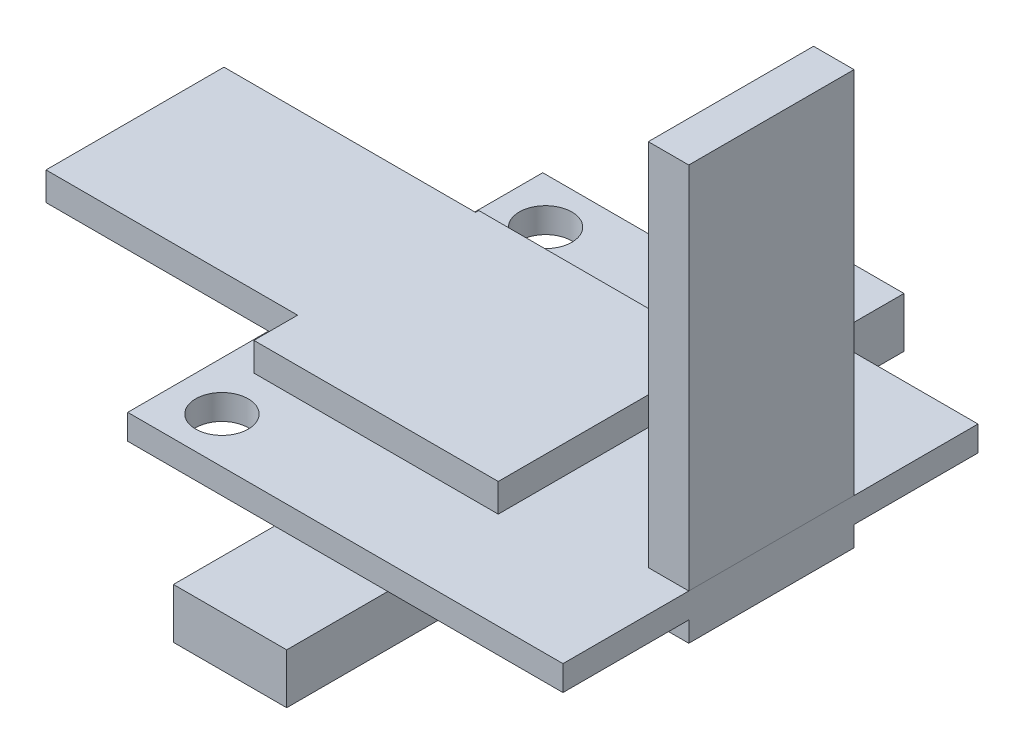
SolidWorks part; units mm, degrees
ref_plane "Front Plane" through (0, 0, 0) normal (0, 0, 1) x (1, 0, 0)
ref_plane "Top Plane" through (0, 0, 0) normal (0, 1, 0) x (1, 0, 0)
ref_plane "Right Plane" through (0, 0, 0) normal (1, 0, 0) x (0, 0, -1)
sketch "Sketch1" plane through (0, 0, 0) normal (0, 1, 0) x (1, 0, 0)
  line L0 (-13.6652, 0) -> (13.6652, 0) construction
  line L1 (-13.6652, 13.0302) -> (13.6652, 13.0302)
  line L2 (-13.6652, 13.0302) -> (-13.6652, -13.0302)
  line L3 (-13.6652, -13.0302) -> (13.6652, -13.0302)
  line L4 (13.6652, 13.0302) -> (13.6652, -13.0302)
  line L5 (-10.6172, 10.16) -> (-10.6172, 0) construction
  line L6 (-10.6172, 0) -> (-10.6172, -10.16) construction
  circle A0 centre (-10.6172, 10.16) radius 1.651
  circle A1 centre (-10.6172, -10.16) radius 1.651
  point P10 (-10.6172, 11.811)
  point P11 (-10.6172, -11.811)
  point P14 (-10.6172, 8.509)
  point P15 (-10.6172, -8.509)
  point P16 (-12.2682, 10.16)
  dimension "D3" = 3.302
  dimension "D1" = 27.3304
  dimension "D2" = 26.0604
  dimension "D4" = 23.622
  dimension "D5" = 17.018
  dimension "D6" = 1.397
extrude "Boss-Extrude1" add sketch "Sketch1" along normal blind 1.5748
sketch "Sketch2" plane through (0, 1.5748, 0) normal (0, 1, 0) x (1, 0, 0)
  line L0 (-11.8364, 6.985) -> (-27.6352, 6.985)
  line L1 (-11.8364, 7.1882) -> (3.5052, 7.1882)
  line L2 (-11.8364, 7.1882) -> (-11.8364, 6.985)
  line L3 (-11.8364, -6.9342) -> (3.5052, -6.9342)
  line L4 (3.5052, 7.1882) -> (3.5052, -6.9342)
  line L5 (-27.6352, 6.985) -> (-27.6352, -4.191)
  line L6 (-27.6352, -4.191) -> (-11.8364, -4.191)
  line L7 (-11.8364, -4.191) -> (-11.8364, -6.9342)
  line L8 (13.6652, 13.0302) -> (-13.6652, 13.0302) construction
  line L9 (-13.6652, -13.0302) -> (13.6652, -13.0302) construction
  line L10 (13.6652, -13.0302) -> (13.6652, 13.0302) construction
  line L11 (-13.6652, 13.0302) -> (-13.6652, -13.0302) construction
  dimension "D1" = 5.842
  dimension "D2" = 6.096
  dimension "D3" = 10.16
  dimension "D4" = 1.8288
  dimension "D5" = 11.176
  dimension "D6" = 0.2032
  dimension "D7" = 13.97
extrude "Boss-Extrude2" add sketch "Sketch2" along normal blind 1.778 separate body
sketch "Sketch3" plane through (0, 1.5748, 0) normal (0, 1, 0) x (1, 0, 0)
  line L0 (13.6652, -13.0302) -> (13.6652, 13.0302) construction
  line L1 (13.6652, 5.2451) -> (11.1252, 5.2451)
  line L2 (13.6652, 5.2451) -> (13.6652, -5.1308)
  line L3 (13.6652, -5.1308) -> (11.1252, -5.1308)
  line L4 (11.1252, 5.2451) -> (11.1252, -5.1308)
  line L5 (13.6652, 13.0302) -> (-13.6652, 13.0302) construction
  line L6 (-13.6652, -13.0302) -> (13.6652, -13.0302) construction
  dimension "D1" = 7.7851
  dimension "D2" = 7.8994
  dimension "D3" = 2.54
extrude "Boss-Extrude3" add sketch "Sketch3" along normal blind 23.1648 separate body
sketch "Sketch4" plane through (0, 0, 0) normal (0, -1, 0) x (1, 0, 0)
  line L0 (-13.6652, 13.0302) -> (13.6652, 13.0302) construction
  line L1 (-4.445, 19.3802) -> (2.667, 19.3802)
  line L2 (-4.445, 19.3802) -> (-4.445, 7.9502)
  line L3 (-4.445, 7.9502) -> (2.667, 7.9502)
  line L4 (2.667, 19.3802) -> (2.667, 7.9502)
  line L5 (-4.445, -7.9502) -> (2.667, -7.9502)
  line L6 (-4.445, -7.9502) -> (-4.445, -19.3802)
  line L7 (-4.445, -19.3802) -> (2.667, -19.3802)
  line L8 (2.667, -7.9502) -> (2.667, -19.3802)
  line L9 (13.6652, 13.0302) -> (13.6652, -13.0302) construction
  line L10 (13.6652, -13.0302) -> (-13.6652, -13.0302) construction
  dimension "D1" = 7.112
  dimension "D2" = 11.43
  dimension "D3" = 6.35
  dimension "D4" = 10.9982
  dimension "D5" = 6.35
extrude "Boss-Extrude4" add sketch "Sketch4" along normal blind 3.1496 separate body
sketch "Sketch5" plane through (0, 0, 0) normal (0, -1, 0) x (1, 0, 0)
  line L1 (11.1252, 5.1308) -> (13.6652, 5.1308)
  line L2 (11.1252, 5.1308) -> (11.1252, -5.2451)
  line L3 (11.1252, -5.2451) -> (13.6652, -5.2451)
  line L4 (13.6652, 5.1308) -> (13.6652, -5.2451)
extrude "Boss-Extrude5" add sketch "Sketch5" along normal blind 1.27
sketch "Sketch6" plane through (0, 0, 0) normal (0, -1, 0) x (1, 0, 0)
  line L0 (-5.0292, 0) -> (5.0292, 0) construction
  line L1 (-5.0292, 4.064) -> (5.0292, 4.064)
  line L2 (-5.0292, 4.064) -> (-5.0292, -4.064)
  line L3 (-5.0292, -4.064) -> (5.0292, -4.064)
  line L4 (5.0292, 4.064) -> (5.0292, -4.064)
  line L5 (13.6652, 13.0302) -> (13.6652, 5.1308) construction
  dimension "D1" = 8.128
  dimension "D2" = 8.636
extrude "Boss-Extrude6" add sketch "Sketch6" along normal blind 1.143 separate body
